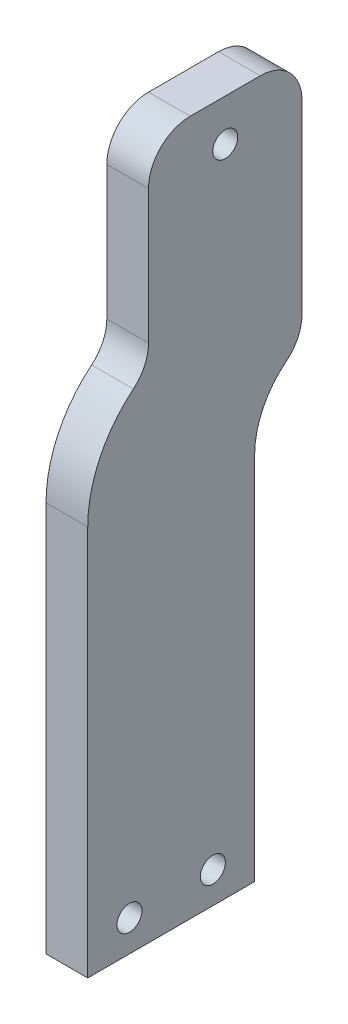
SolidWorks part; units mm, degrees
ref_plane "Спереди" through (0, 0, 0) normal (0, 0, 1) x (1, 0, 0)
ref_plane "Сверху" through (0, 0, 0) normal (0, 1, 0) x (1, 0, 0)
ref_plane "Справа" through (0, 0, 0) normal (1, 0, 0) x (0, 0, -1)
sketch "Эскиз1" plane through (0, 0, 0) normal (1, 0, 0) x (0, 0, -1)
  line L2 (-19.9999, 63.4837) -> (-19.9999, -30.1439)
  line L3 (-19.9999, -30.1439) -> (20.0001, -30.1439)
  line L4 (20.0001, 58.3956) -> (20.0001, -30.1439)
  line L5 (-5.4307, 94.3588) -> (-5.4307, 126.4532)
  line L6 (40.9616, 134.4532) -> (-15.0384, 134.4532) construction
  line L7 (4.5693, 136.4532) -> (21.3539, 136.4532)
  line L8 (31.3539, 126.4532) -> (31.3539, 81.8971)
  arc A0 (20.0001, 58.3956) -> (27.5693, 74.0633) centre (40.0001, 58.3956) cw
  arc A1 (-19.9999, 63.4837) -> (-9.073, 86.6401) centre (10.0001, 63.4837) cw
  arc A2 (27.5693, 74.0633) -> (31.3539, 81.8971) centre (21.3539, 81.8971) ccw
  arc A3 (-9.073, 86.6401) -> (-5.4307, 94.3588) centre (-15.4307, 94.3588) ccw
  arc A4 (31.3539, 126.4532) -> (21.3539, 136.4532) centre (21.3539, 126.4532) ccw
  arc A5 (-5.4307, 126.4532) -> (4.5693, 136.4532) centre (4.5693, 126.4532) cw
  point P22 (8.6411, 134.4532)
  dimension "D1" = 40
  dimension "D2" = 20
  dimension "D3" = 30
  dimension "D4" = 10
  dimension "D5" = 10
  dimension "D6" = 10
extrude "Вытянуть1" add sketch "Эскиз1" along normal blind 10
sketch "Эскиз2" plane through (0, 0, 0) normal (-1, 0, 0) x (0, 0, 1)
  circle A0 centre (10, -22.6439) radius 3
  circle A1 centre (-10, -22.6439) radius 3
  circle A2 centre (-12.9616, 126.4532) radius 3
  dimension "D1" = 6
extrude "Вырез-Вытянуть1" cut sketch "Эскиз2" against normal blind 25
